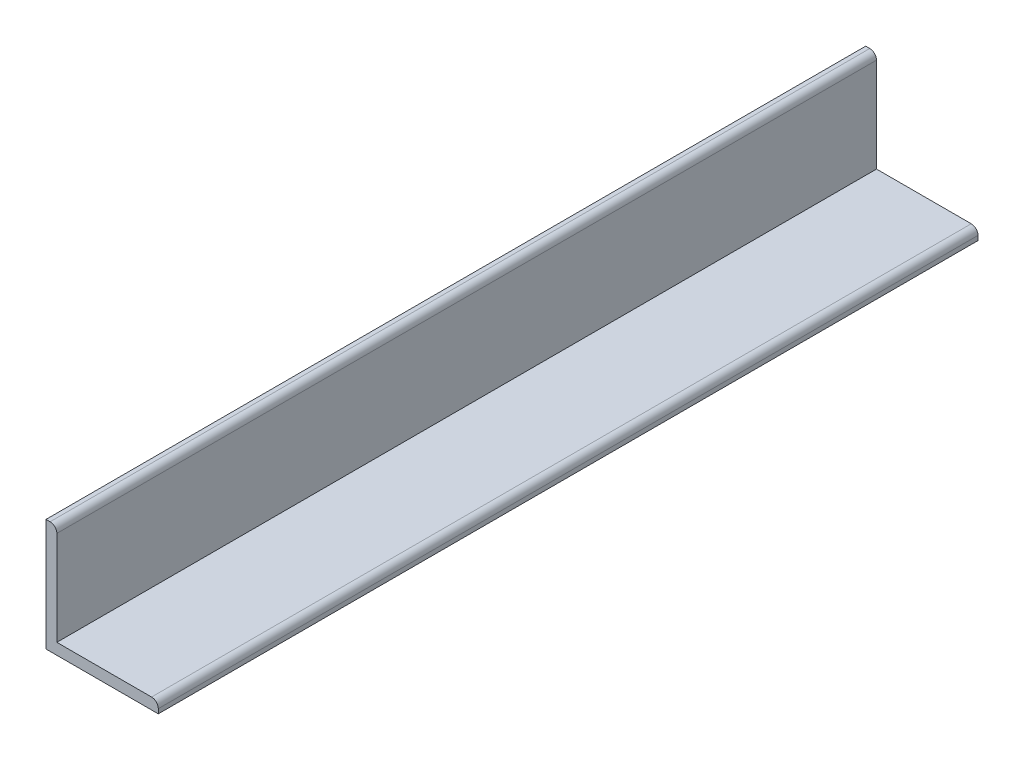
SolidWorks part; units mm, degrees
material "ASTM A36 Steel"
ref_plane "Front Plane" through (0, 0, 0) normal (0, 0, 1) x (1, 0, 0)
ref_plane "Top Plane" through (0, 0, 0) normal (0, 1, 0) x (1, 0, 0)
ref_plane "Right Plane" through (0, 0, 0) normal (1, 0, 0) x (0, 0, -1)
sketch "Sketch1" plane through (0, 0, 0) normal (0, 0, 1) x (1, 0, 0)
  line L0 (-19.7246, 21.5464) -> (-19.7246, -20.4536)
  line L1 (-24.5464, -25.4536) -> (25.4536, -25.4536)
  line L2 (-24.5464, -25.4536) -> (-24.5464, 24.5464)
  line L3 (-24.5464, 24.5464) -> (-22.7246, 24.5464)
  line L4 (25.4536, -25.4536) -> (25.4536, -23.4536)
  line L5 (-24.5464, -25.4536) -> (24.5383, 25.4452) construction
  line L6 (-24.5464, 24.5464) -> (25.4536, -25.4536) construction
  line L7 (-19.7246, -20.4536) -> (22.4536, -20.4536)
  arc A0 (22.4536, -20.4536) -> (25.4536, -23.4536) centre (22.4536, -23.4536) cw
  arc A1 (-19.7246, 21.5464) -> (-22.7246, 24.5464) centre (-22.7246, 21.5464) ccw
  point P0 (0, 0)
  dimension "D4" = 3
  dimension "D1" = 50
  dimension "D2" = 50
  dimension "D3" = 5
extrude "Boss-Extrude1" add sketch "Sketch1" along normal mid plane 365
